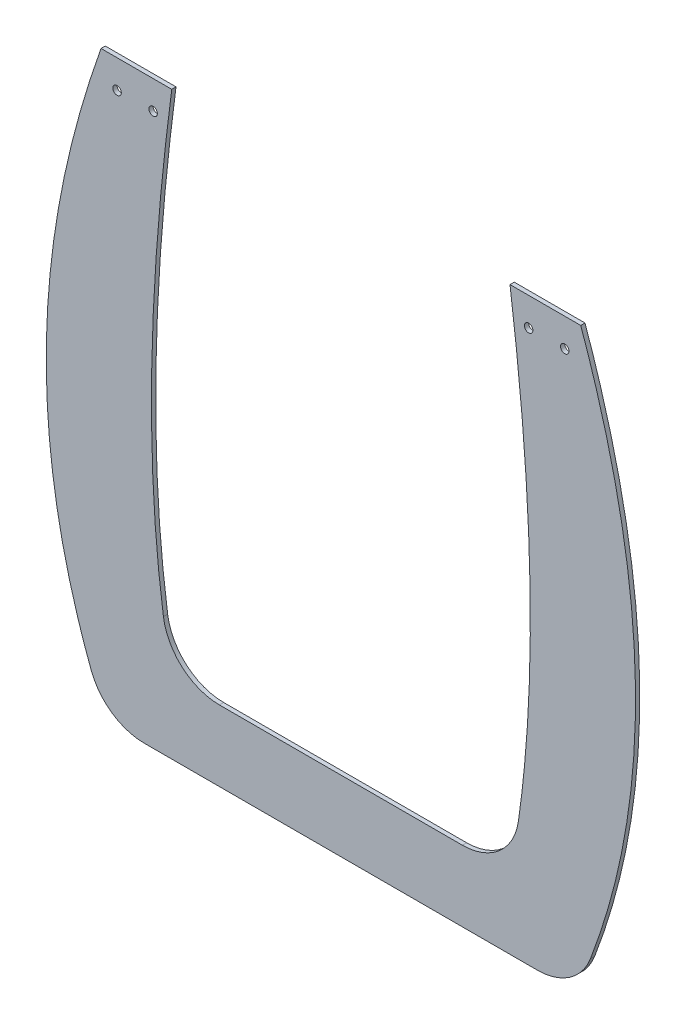
SolidWorks part; units mm, degrees
ref_plane "Front Plane" through (0, 0, 0) normal (0, 0, 1) x (1, 0, 0)
ref_plane "Top Plane" through (0, 0, 0) normal (0, 1, 0) x (1, 0, 0)
ref_plane "Right Plane" through (0, 0, 0) normal (1, 0, 0) x (0, 0, -1)
sketch "Sketch1" plane through (0, 0, 0) normal (0, 0, 1) x (1, 0, 0)
  line L0 (-4.3116, 0) -> (20.6884, 0)
  line L1 (-123.8484, 0) -> (-148.8484, 0)
  line L2 (-4.3116, -180) -> (-123.8484, -180)
  line L3 (-64.08, -205) -> (-64.08, -147.3243) construction
  line L4 (-146.9792, -205) -> (18.8192, -205)
  circle A0 centre (2.285, -10) radius 1.5
  circle A1 centre (15.025, -10) radius 1.5
  circle A4 centre (-143.185, -10) radius 1.5
  circle A5 centre (-130.445, -10) radius 1.5
  spline S0 degree 2 poles (20.6884, 0) (60.3128, -111.602) (18.8192, -205) knots 0 0 0 0.947972 0.947972 0.947972
  spline S1 degree 2 poles (-4.3116, 0) (10.0422, -108.5928) (-4.3116, -180) knots 0 0 0 0.806546 0.806546 0.806546
  spline S2 degree 2 poles (-123.8484, 0) (-138.2022, -108.5928) (-123.8484, -180) knots 0 0 0 0.806546 0.806546 0.806546
  spline S3 degree 2 poles (-148.8484, 0) (-188.4728, -111.602) (-146.9792, -205) knots 0 0 0 0.947972 0.947972 0.947972
  point P19 (0, 0)
  point P20 (-4.3116, 0)
  dimension "D5" = 180.7798
  dimension "D6" = 145.6711
  dimension "D7" = 12.74
  dimension "D8" = 3
  dimension "D9" = 3
  dimension "D10" = 10
  dimension "D2" = 66.365
  dimension "D1" = 25
  dimension "D3" = 180
extrude "Boss-Extrude1" add sketch "Sketch1" along normal blind 1.5
fillet "Fillet1" radius 20 2 edges at (-123.8484, -180, 0.75) (-4.3116, -180, 0.75)
fillet "Fillet2" radius 20 2 edges at (-146.9792, -205, 0.75) (18.8192, -205, 0.75)
